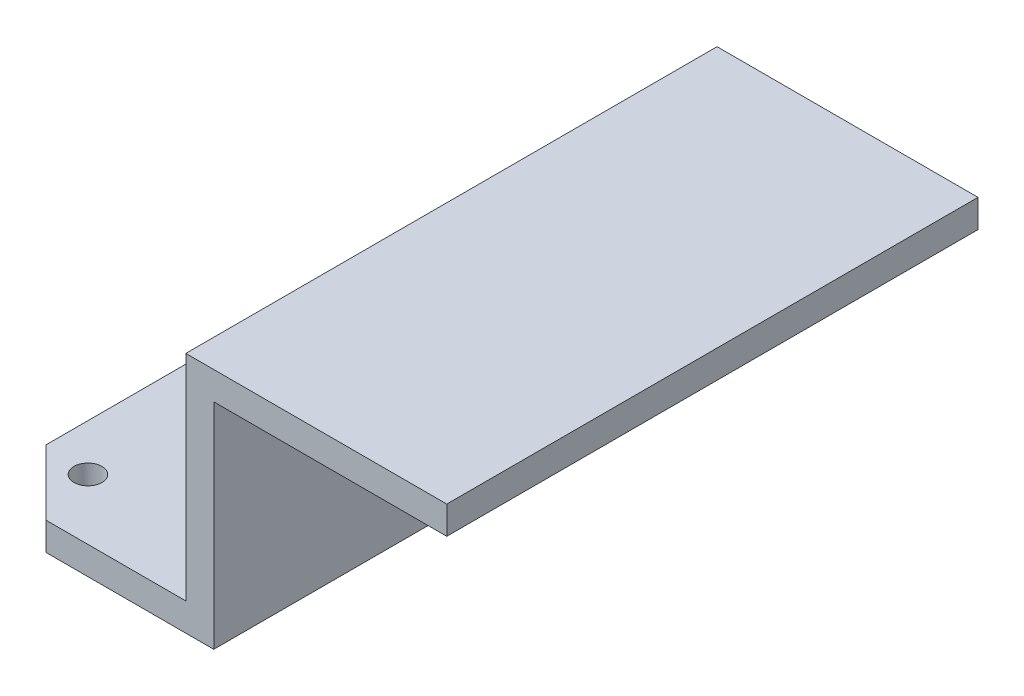
SolidWorks part; units mm, degrees
ref_plane "Piano frontale" through (0, 0, 0) normal (0, 0, 1) x (1, 0, 0)
ref_plane "Piano superiore" through (0, 0, 0) normal (0, 1, 0) x (1, 0, 0)
ref_plane "Piano destro" through (0, 0, 0) normal (1, 0, 0) x (0, 0, -1)
sketch "Schizzo1" plane through (0, 0, 0) normal (0, 0, 1) x (1, 0, 0)
  line L0 (0, 0) -> (20, 0)
  line L1 (20, 0) -> (20, 23)
  line L2 (20, 23) -> (45, 23)
  line L3 (0, 0) -> (-5, 0)
  line L4 (-5, 0) -> (-5, 3)
  line L5 (-5, 3) -> (17, 3)
  line L6 (17, 3) -> (17, 26)
  line L7 (17, 26) -> (45, 26)
  line L8 (45, 26) -> (45, 23)
extrude "Estrusione-Estrusione1" add sketch "Schizzo1" along normal blind 57
sketch "Schizzo2" plane through (0, 3, 0) normal (0, 1, 0) x (1, 0, 0)
  line L0 (0, 0) -> (0, -57) construction
  line L1 (17, -57) -> (-5, -57) construction
  line L2 (0, -6.5) -> (0, -50.5) construction
  circle A0 centre (0, -50.5) radius 1.5
  circle A1 centre (0, -6.5) radius 1.5
  point P8 (0, -28.5)
extrude "Taglio-Estrusione1" cut sketch "Schizzo2" against normal blind 57
chamfer "Smusso1" distance 7 angle 45 2 edges at (-5, 1.5, 0) (-5, 1.5, 57)
